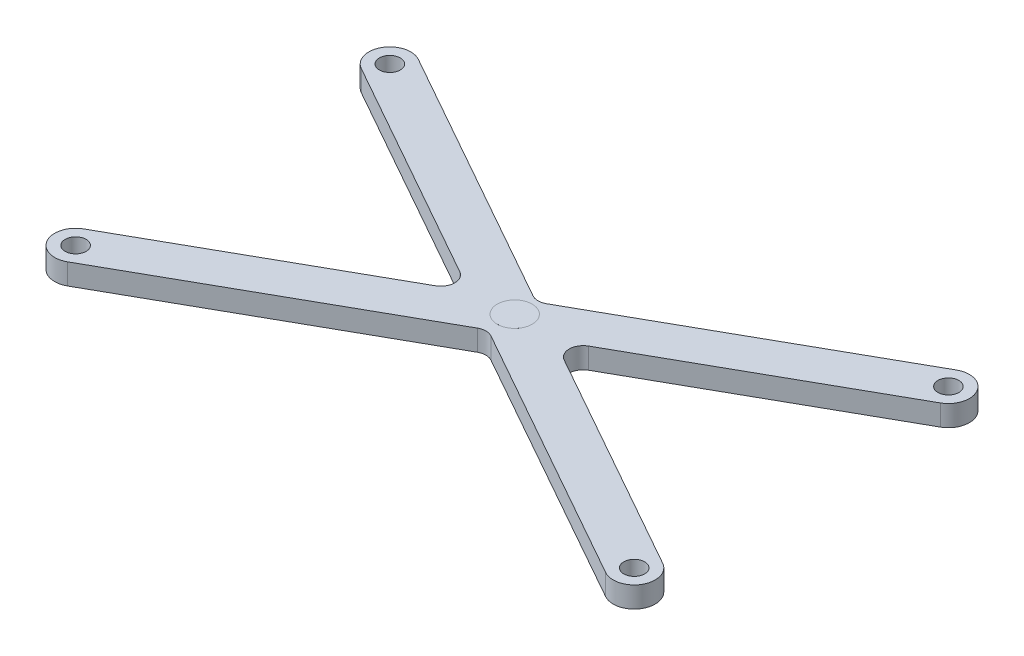
SolidWorks part; units mm, degrees
material "Cast Alloy Steel"
ref_plane "Front Plane" through (0, 0, 0) normal (0, 0, 1) x (1, 0, 0)
ref_plane "Top Plane" through (0, 0, 0) normal (0, 1, 0) x (1, 0, 0)
ref_plane "Right Plane" through (0, 0, 0) normal (1, 0, 0) x (0, 0, -1)
sketch "Sketch1" plane through (0, 0, 0) normal (0, 1, 0) x (1, 0, 0)
  line L0 (0, 45) -> (80, 0) construction
  line L1 (0, 0) -> (80, 0) construction
  line L2 (0, 0) -> (0, 45) construction
  line L3 (0, 45) -> (80, 45) construction
  line L4 (80, 0) -> (80, 45) construction
  line L5 (1.4701, 47.6151) -> (39.0195, 26.4936)
  line L6 (-1.4718, 42.3859) -> (30.7819, 24.2432)
  line L7 (0, 0) -> (80, 45) construction
  line L8 (-1.4718, 2.6141) -> (30.7819, 20.7568)
  line L9 (1.4701, -2.6151) -> (39.0195, 18.5064)
  line L10 (40.9805, 26.4936) -> (78.5299, 47.6151)
  line L11 (49.2181, 20.7568) -> (81.4718, 2.6141)
  line L12 (49.2181, 24.2432) -> (81.4718, 42.3859)
  line L13 (40.9805, 18.5064) -> (78.5299, -2.6151)
  line L15 (46.1173, 25.941) -> (33.8827, 25.941) construction
  line L16 (46.1173, 25.941) -> (46.1173, 19.059) construction
  line L17 (46.1173, 19.059) -> (33.8827, 19.059) construction
  line L18 (33.8827, 25.941) -> (33.8827, 19.059) construction
  line L19 (46.1173, 25.941) -> (33.8827, 19.059) construction
  line L20 (46.1173, 19.059) -> (33.8827, 25.941) construction
  arc A0 (1.4701, 47.6151) -> (-1.4718, 42.3859) centre (0, 45) ccw
  arc A1 (78.5299, -2.6151) -> (81.4718, 2.6141) centre (80, 0) ccw
  arc A2 (-1.4718, 2.6141) -> (1.4701, -2.6151) centre (0, 0) ccw
  arc A3 (81.4718, 42.3859) -> (78.5299, 47.6151) centre (80, 45) ccw
  circle A4 centre (0, 45) radius 1.5
  circle A5 centre (80, 45) radius 1.5
  circle A6 centre (80, 0) radius 1.5
  circle A7 centre (0, 0) radius 1.5
  arc A8 (39.0195, 18.5064) -> (40.9805, 18.5064) centre (40, 16.7633) cw
  arc A9 (40.9805, 26.4936) -> (39.0195, 26.4936) centre (40, 28.2367) cw
  arc A10 (49.2181, 20.7568) -> (49.2181, 24.2432) centre (50.1986, 22.5) cw
  arc A11 (30.7819, 20.7568) -> (30.7819, 24.2432) centre (29.8014, 22.5) ccw
  point P5 (40, 22.5)
  point P10 (40, 22.5)
  point P16 (40, 22.5)
  point P30 (40, 19.058)
  point P33 (40, 25.942)
  point P36 (46.1192, 22.5)
  point P39 (33.8808, 22.5)
  dimension "D3" = 3
  dimension "D4" = 3
  dimension "D5" = 3
  dimension "D6" = 3
  dimension "D10" = 3
  dimension "D11" = 2
  dimension "D1" = 45
  dimension "D2" = 80
  dimension "D7" = 40.5618
  dimension "D8" = 44.2072
  dimension "D9" = 6.8819
extrude "Boss-Extrude1" add sketch "Sketch1" along normal blind 3
sketch "Sketch2" plane through (0, 3, 0) normal (0, 1, 0) x (1, 0, 0)
  circle A0 centre (39.9795, 22.9097) radius 2.5
  dimension "D1" = 5
extrude "Boss-Extrude2" add sketch "Sketch2" along normal blind 0.001
